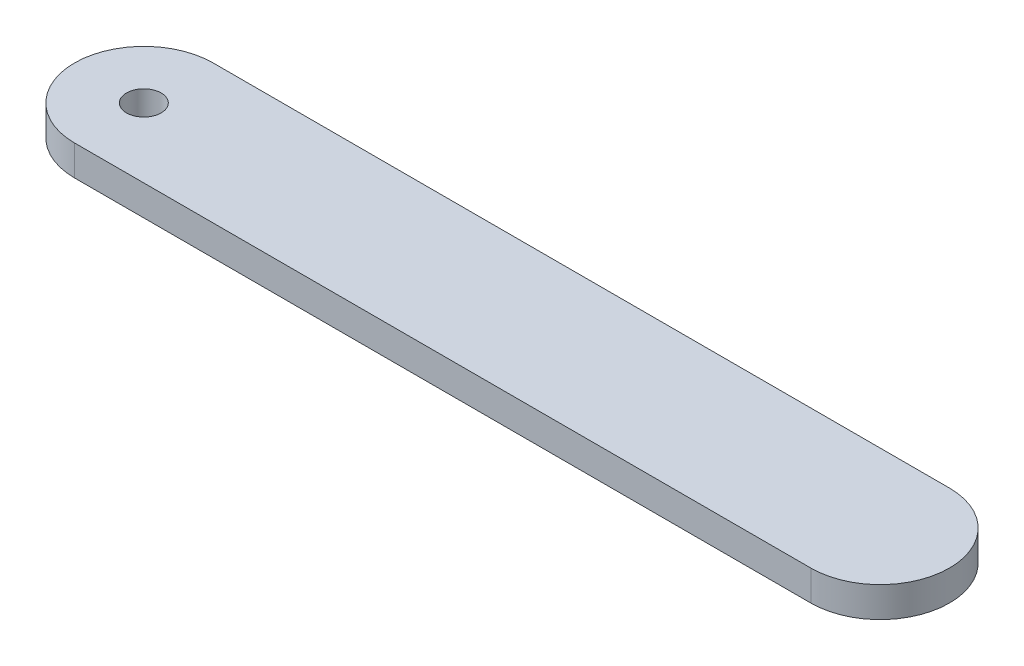
SolidWorks part; units mm, degrees
ref_plane "Front Plane" through (0, 0, 0) normal (0, 0, 1) x (1, 0, 0)
ref_plane "Top Plane" through (0, 0, 0) normal (0, 1, 0) x (1, 0, 0)
ref_plane "Right Plane" through (0, 0, 0) normal (1, 0, 0) x (0, 0, -1)
sketch "Sketch1" plane through (0, 0, 0) normal (0, 1, 0) x (1, 0, 0)
  line L0 (0, 0) -> (85, 0) construction
  line L1 (0, 8) -> (85, 8)
  line L2 (0, -8) -> (85, -8)
  arc A0 (0, 8) -> (0, -8) centre (0, 0) ccw
  arc A1 (85, -8) -> (85, 8) centre (85, 0) ccw
  point P3 (42.5, 0)
  dimension "D1" = 85
  dimension "0.8" = 8
extrude "Boss-Extrude1" add sketch "Sketch1" along normal blind 3.5
sketch "Sketch2" plane through (0, 3.5, 0) normal (0, 1, 0) x (1, 0, 0)
  circle A0 centre (0, 0) radius 2
  dimension "D1" = 4
extrude "Cut-Extrude1" cut sketch "Sketch2" against normal blind 3.5
